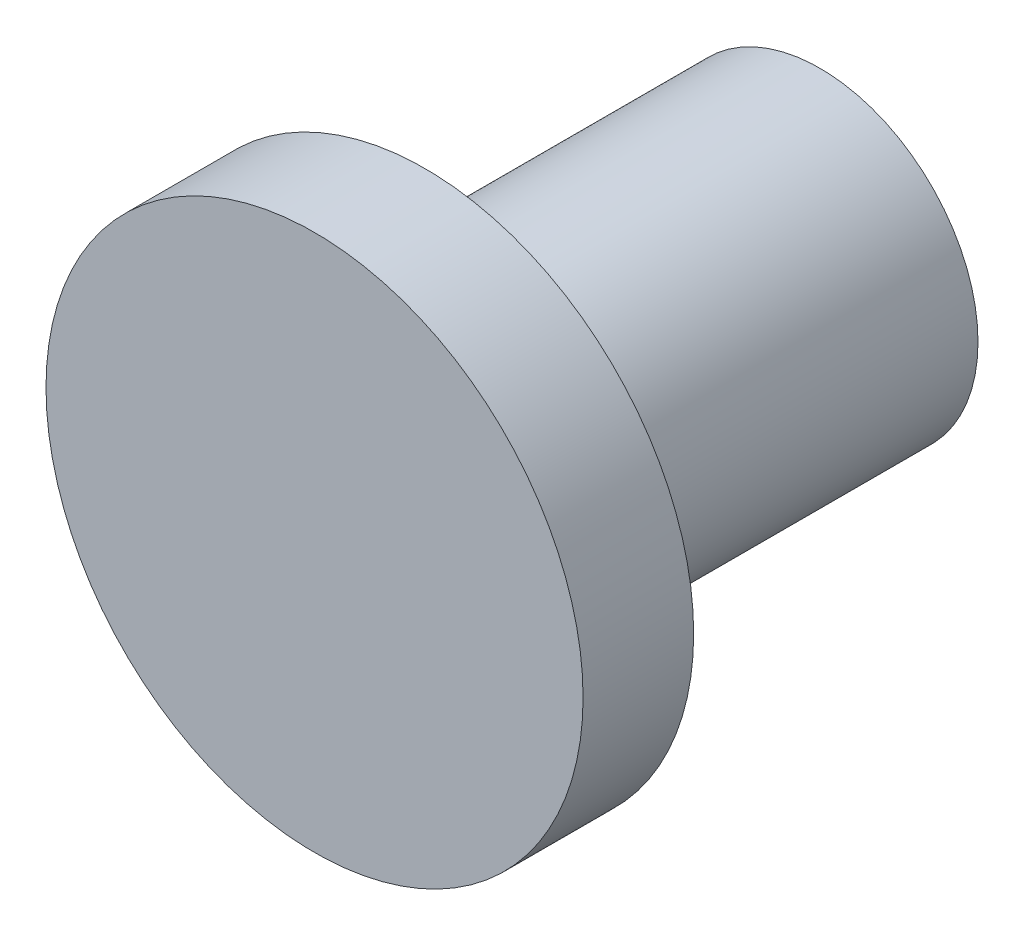
SolidWorks part; units mm, degrees
ref_plane "Front Plane" through (0, 0, 0) normal (0, 0, 1) x (1, 0, 0)
ref_plane "Top Plane" through (0, 0, 0) normal (0, 1, 0) x (1, 0, 0)
ref_plane "Right Plane" through (0, 0, 0) normal (1, 0, 0) x (0, 0, -1)
sketch "Sketch1" plane through (0, 0, 0) normal (0, 0, 1) x (1, 0, 0)
  circle A0 centre (0, 0) radius 1
extrude "Thread_Envelope" add sketch "Sketch1" along normal blind 2.5 from offset 2.5
sketch "Sketch2" plane through (0, 0, 0) normal (0, 0, 1) x (1, 0, 0)
  circle A0 centre (0, 0) radius 1.7
extrude "Head_Envelope" add sketch "Sketch2" along normal blind 0.7
